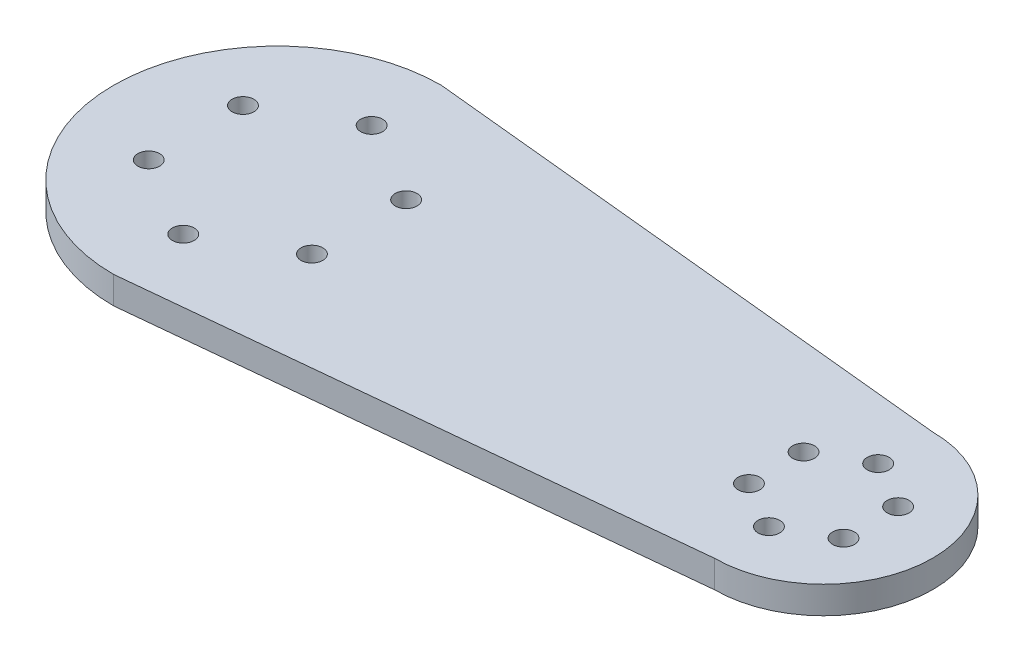
SolidWorks part; units mm, degrees
ref_plane "前视基准面" through (0, 0, 0) normal (0, 0, 1) x (1, 0, 0)
ref_plane "上视基准面" through (0, 0, 0) normal (0, 1, 0) x (1, 0, 0)
ref_plane "右视基准面" through (0, 0, 0) normal (1, 0, 0) x (0, 0, -1)
other "Configuration Table"
sketch "草图1" plane through (0, 0, 0) normal (0, 1, 0) x (1, 0, 0)
  line L0 (0, 0) -> (100, 0)
  line L1 (0, 30) -> (100, 20)
  line L2 (0, -30) -> (100, -20)
  circle A0 centre (0, 0) radius 30
  circle A1 centre (0, 0) radius 17.25
  circle A2 centre (0, 17.25) radius 2
  circle A3 centre (14.9389, 8.625) radius 2
  circle A4 centre (14.9389, -8.625) radius 2
  circle A5 centre (0, -17.25) radius 2
  circle A6 centre (-14.9389, -8.625) radius 2
  circle A7 centre (-14.9389, 8.625) radius 2
  circle A8 centre (100, 0) radius 20
  circle A9 centre (100, 0) radius 10
  circle A10 centre (100, 10) radius 2
  circle A11 centre (108.6603, 5) radius 2
  circle A12 centre (108.6603, -5) radius 2
  circle A13 centre (100, -10) radius 2
  circle A14 centre (91.3397, -5) radius 2
  circle A15 centre (91.3397, 5) radius 2
  dimension "D1" = 60
  dimension "D2" = 34.5
  dimension "D3" = 4
  dimension "D6" = 40
  dimension "D7" = 20
  dimension "D8" = 4
  dimension "D5" = 100
  dimension "D4" = 6
  dimension "D9" = 6
extrude "凸台-拉伸1" add sketch "草图1" along normal blind 5
